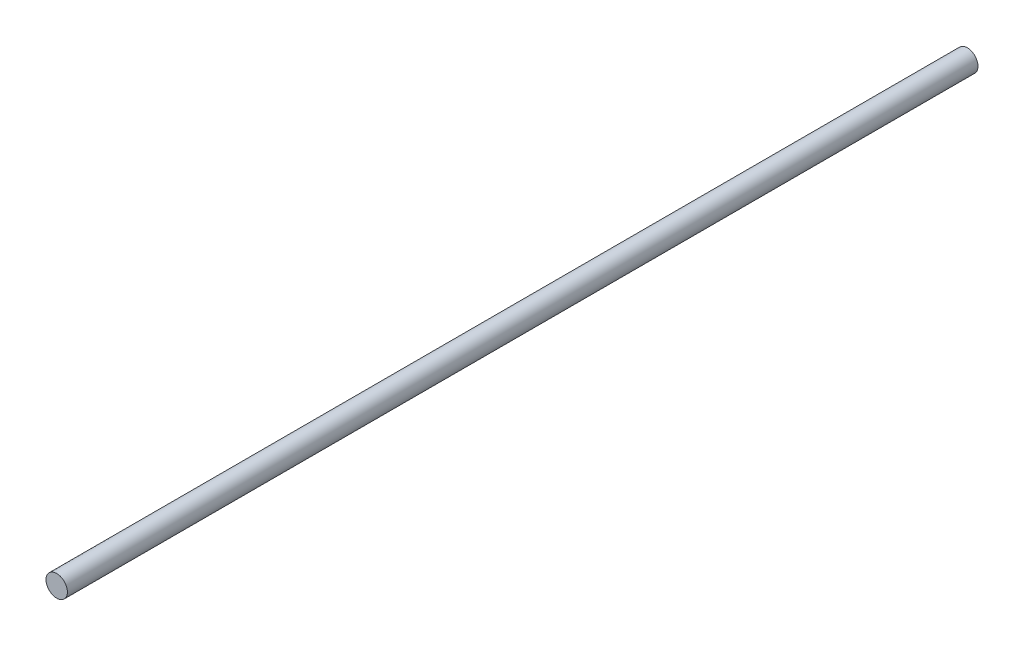
SolidWorks part; units mm, degrees
ref_plane "Front Plane" through (0, 0, 0) normal (0, 0, 1) x (1, 0, 0)
ref_plane "Top Plane" through (0, 0, 0) normal (0, 1, 0) x (1, 0, 0)
ref_plane "Right Plane" through (0, 0, 0) normal (1, 0, 0) x (0, 0, -1)
sketch "Sketch1" plane through (0, 0, 0) normal (0, 0, 1) x (1, 0, 0)
  circle A0 centre (0, 0) radius 2
  dimension "D1" = 4
extrude "Boss-Extrude1" add sketch "Sketch1" along normal mid plane 170
